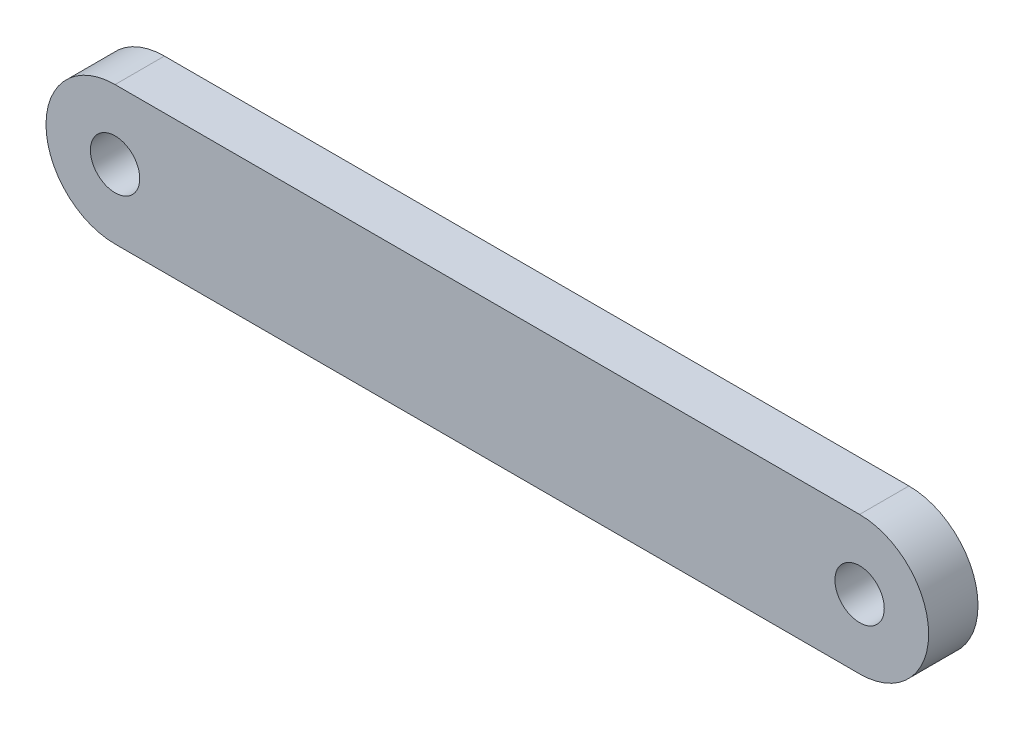
SolidWorks part; units mm, degrees
ref_plane "Front Plane" through (0, 0, 0) normal (0, 0, 1) x (1, 0, 0)
ref_plane "Top Plane" through (0, 0, 0) normal (0, 1, 0) x (1, 0, 0)
ref_plane "Right Plane" through (0, 0, 0) normal (1, 0, 0) x (0, 0, -1)
sketch "Sketch2" plane through (0, 0, 0) normal (0, 0, 1) x (1, 0, 0)
  line L0 (-63.1952, -8.8071) -> (32.639, -8.8071)
  line L1 (-63.1952, 8.9729) -> (32.639, 8.9729)
  line L2 (-63.1952, -8.8071) -> (32.639, 8.9729) construction
  line L3 (-63.1952, 8.9729) -> (32.639, -8.8071) construction
  arc A0 (-63.1952, 8.9729) -> (-63.1952, -8.8071) centre (-63.1952, 0.0829) ccw
  arc A1 (32.639, 8.9729) -> (32.639, -8.8071) centre (32.639, 0.0829) cw
  circle A2 centre (-63.1952, 0.0829) radius 3.175
  circle A3 centre (32.639, 0.0829) radius 3.175
  point P0 (-15.2781, 0.0829)
  dimension "D3" = 6.35
  dimension "D1" = 95.8342
  dimension "D2" = 17.78
extrude "Boss-Extrude2" add sketch "Sketch2" along normal blind 6.35
